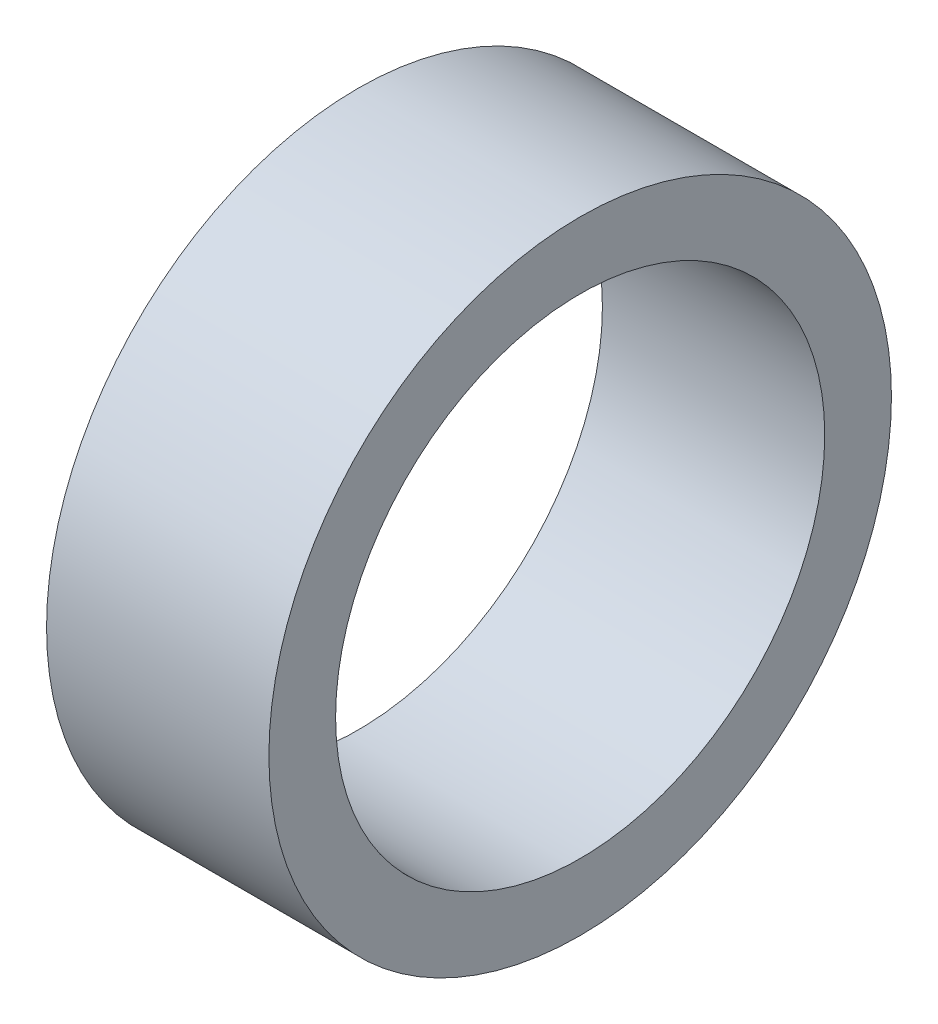
SolidWorks part; units mm, degrees
ref_plane "Front Plane" through (0, 0, 0) normal (0, 0, 1) x (1, 0, 0)
ref_plane "Top Plane" through (0, 0, 0) normal (0, 1, 0) x (1, 0, 0)
ref_plane "Right Plane" through (0, 0, 0) normal (1, 0, 0) x (0, 0, -1)
sketch "Sketch1" plane through (0, 0, 0) normal (1, 0, 0) x (0, 0, -1)
  circle A0 centre (0, 0) radius 3.4925
  circle A1 centre (0, 0) radius 4.445
  dimension "D1" = 6.985
  dimension "D2" = 8.89
extrude "Boss-Extrude1" add sketch "Sketch1" along normal blind 3.175
